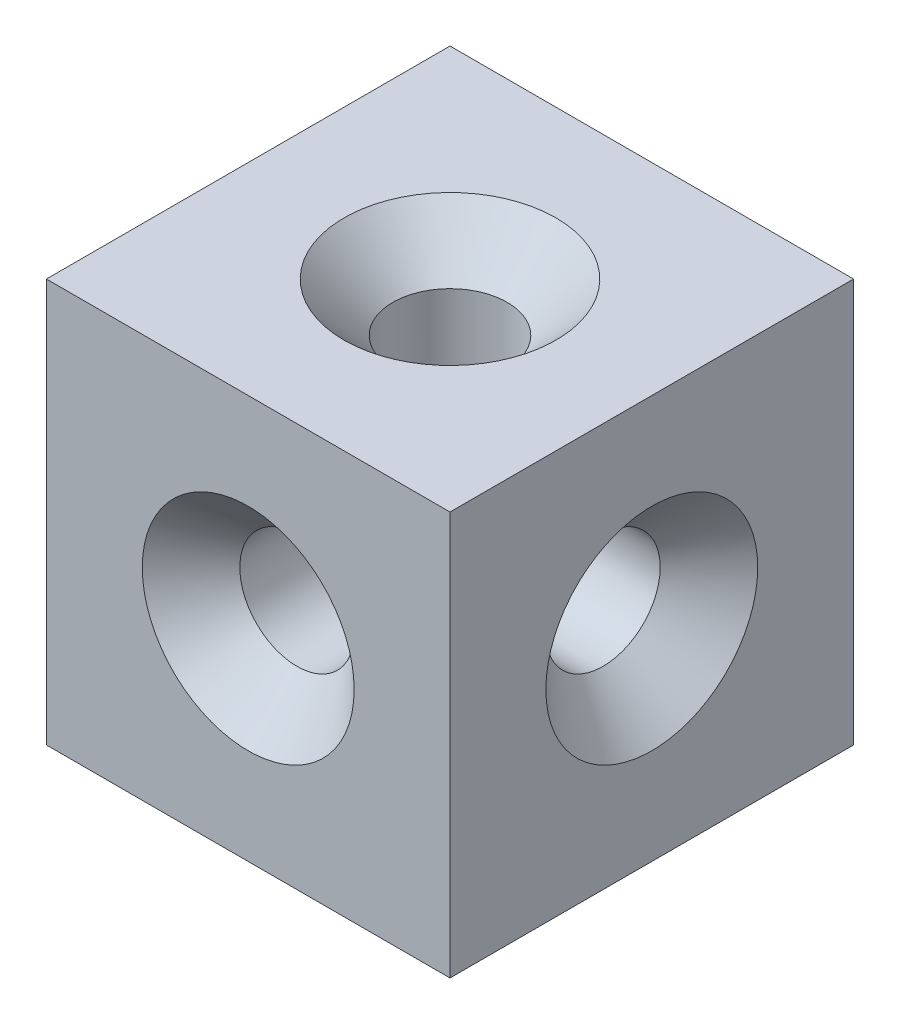
SolidWorks part; units mm, degrees
ref_plane "Front Plane" through (0, 0, 0) normal (0, 0, 1) x (1, 0, 0)
ref_plane "Top Plane" through (0, 0, 0) normal (0, 1, 0) x (1, 0, 0)
ref_plane "Right Plane" through (0, 0, 0) normal (1, 0, 0) x (0, 0, -1)
sketch "Sketch1" plane through (0, 0, 0) normal (0, 0, 1) x (1, 0, 0)
  line L1 (6, -6) -> (-6, -6)
  line L2 (6, -6) -> (6, 6)
  line L3 (6, 6) -> (-6, 6)
  line L4 (-6, -6) -> (-6, 6)
  line L5 (6, -6) -> (-6, 6) construction
  line L6 (6, 6) -> (-6, -6) construction
  point P0 (0, 0)
  dimension "D1" = 12
  dimension "D2" = 12
extrude "Boss-Extrude1" add sketch "Sketch1" along normal mid plane 12
hole_wizard "CSK for M3 Flat Head Machine Screw1" positions "Sketch3" profile "Sketch2" countersink size "M3" standard "ANSI Metric"
sketch "Sketch3" plane through (0, 0, 6) normal (0, 0, 1) x (1, 0, 0)
  point P0 (0, 0)
sketch "Sketch2" plane through (0, 0, 6) normal (1, 0, 0) x (0, -1, 0)
  line L0 (0, 0) -> (0, 7.0215)
  line L1 (0, 7.0215) -> (1.7, 6)
  line L2 (1.7, 6) -> (1.7, 1.45)
  line L3 (1.7, 1.45) -> (3.15, 0)
  line L5 (3.15, 0) -> (0, 0)
  line L6 (-1.7, 1.45) -> (-3.15, 0) construction
  line L10 (0, 7.0215) -> (-1.7, 6) construction
  line L11 (0, -6.35) -> (0, 107.95) construction
  dimension "Hole Dia." = 3.4
  dimension "Hole Depth" = 6
  dimension "Near C'Sink Dia." = 6.3
  dimension "Near C'Sink Angle" = 90
  dimension "Drill Angle" = 118
hole_wizard "CSK for M3 Flat Head Machine Screw2" positions "Sketch6" profile "Sketch7" countersink size "M3" standard "ANSI Metric"
sketch "Sketch6" plane through (6, 0, 0) normal (1, 0, 0) x (0, 0, -1)
  point P0 (0, 0)
sketch "Sketch7" plane through (6, 0, 0) normal (0, 1, 0) x (0, 0, -1)
  line L0 (0, 0) -> (0, 7.0215)
  line L1 (0, 7.0215) -> (1.7, 6)
  line L2 (1.7, 6) -> (1.7, 1.45)
  line L3 (1.7, 1.45) -> (3.15, 0)
  line L5 (3.15, 0) -> (0, 0)
  line L6 (-1.7, 1.45) -> (-3.15, 0) construction
  line L10 (0, 7.0215) -> (-1.7, 6) construction
  line L11 (0, -6.35) -> (0, 107.95) construction
  dimension "Hole Dia." = 3.4
  dimension "Hole Depth" = 6
  dimension "Near C'Sink Dia." = 6.3
  dimension "Near C'Sink Angle" = 90
  dimension "Drill Angle" = 118
hole_wizard "CSK for M3 Flat Head Machine Screw3" positions "Sketch8" profile "Sketch9" countersink size "M3" standard "ANSI Metric"
sketch "Sketch8" plane through (0, 0, -6) normal (0, 0, -1) x (-1, 0, 0)
  point P0 (0, 0)
sketch "Sketch9" plane through (0, 0, -6) normal (1, 0, 0) x (0, 1, 0)
  line L0 (0, 0) -> (0, 7.0215)
  line L1 (0, 7.0215) -> (1.7, 6)
  line L2 (1.7, 6) -> (1.7, 1.45)
  line L3 (1.7, 1.45) -> (3.15, 0)
  line L5 (3.15, 0) -> (0, 0)
  line L6 (-1.7, 1.45) -> (-3.15, 0) construction
  line L10 (0, 7.0215) -> (-1.7, 6) construction
  line L11 (0, -6.35) -> (0, 107.95) construction
  dimension "Hole Dia." = 3.4
  dimension "Hole Depth" = 6
  dimension "Near C'Sink Dia." = 6.3
  dimension "Near C'Sink Angle" = 90
  dimension "Drill Angle" = 118
hole_wizard "CSK for M3 Flat Head Machine Screw7" positions "Sketch10" profile "Sketch11" countersink size "M3" standard "ANSI Metric"
sketch "Sketch10" plane through (-6, 0, 0) normal (-1, 0, 0) x (0, 0, 1)
  point P0 (0, 0)
  point P4 (0, 0)
sketch "Sketch11" plane through (-6, 0, 0) normal (0, 1, 0) x (0, 0, 1)
  line L0 (0, 0) -> (0, 7.0215)
  line L1 (0, 7.0215) -> (1.7, 6)
  line L2 (1.7, 6) -> (1.7, 1.45)
  line L3 (1.7, 1.45) -> (3.15, 0)
  line L5 (3.15, 0) -> (0, 0)
  line L6 (-1.7, 1.45) -> (-3.15, 0) construction
  line L10 (0, 7.0215) -> (-1.7, 6) construction
  line L11 (0, -6.35) -> (0, 107.95) construction
  dimension "Hole Dia." = 3.4
  dimension "Hole Depth" = 6
  dimension "Near C'Sink Dia." = 6.3
  dimension "Near C'Sink Angle" = 90
  dimension "Drill Angle" = 118
hole_wizard "CSK for M3 Flat Head Machine Screw8" positions "Sketch12" profile "Sketch13" countersink size "M3" standard "ANSI Metric"
sketch "Sketch12" plane through (0, 6, 0) normal (0, 1, 0) x (1, 0, 0)
  point P0 (0, 0)
sketch "Sketch13" plane through (0, 6, 0) normal (1, 0, 0) x (0, 0, 1)
  line L0 (0, 0) -> (0, 7.0215)
  line L1 (0, 7.0215) -> (1.7, 6)
  line L2 (1.7, 6) -> (1.7, 1.45)
  line L3 (1.7, 1.45) -> (3.15, 0)
  line L5 (3.15, 0) -> (0, 0)
  line L6 (-1.7, 1.45) -> (-3.15, 0) construction
  line L10 (0, 7.0215) -> (-1.7, 6) construction
  line L11 (0, -6.35) -> (0, 107.95) construction
  dimension "Hole Dia." = 3.4
  dimension "Hole Depth" = 6
  dimension "Near C'Sink Dia." = 6.3
  dimension "Near C'Sink Angle" = 90
  dimension "Drill Angle" = 118
hole_wizard "CSK for M3 Flat Head Machine Screw9" positions "Sketch14" profile "Sketch15" countersink size "M3" standard "ANSI Metric"
sketch "Sketch14" plane through (0, -6, 0) normal (0, -1, 0) x (-1, 0, 0)
  point P0 (0, 0)
sketch "Sketch15" plane through (0, -6, 0) normal (1, 0, 0) x (0, 0, -1)
  line L0 (0, 0) -> (0, 7.0215)
  line L1 (0, 7.0215) -> (1.7, 6)
  line L2 (1.7, 6) -> (1.7, 1.45)
  line L3 (1.7, 1.45) -> (3.15, 0)
  line L5 (3.15, 0) -> (0, 0)
  line L6 (-1.7, 1.45) -> (-3.15, 0) construction
  line L10 (0, 7.0215) -> (-1.7, 6) construction
  line L11 (0, -6.35) -> (0, 107.95) construction
  dimension "Hole Dia." = 3.4
  dimension "Hole Depth" = 6
  dimension "Near C'Sink Dia." = 6.3
  dimension "Near C'Sink Angle" = 90
  dimension "Drill Angle" = 118
equation "\"Length\"= 283mm"
equation "\"Width\"= 225mm"
equation "\"WallThickness\"= 12.5mm"
equation "\"UpperWaterJacketThickness\"= 28mm"
equation "\"SpacerHeight\"= 80.2mm"
equation "\"SpacerCornerWidth\"= 10mm"
equation "\"SpacerCornerHeight\"= 60.16mm"
equation "\"SpacerPegDiameter\"= 10mm"
equation "\"SpacerPegHeight\"= 10mm"
equation "\"TubingShort\"= 110mm"
equation "\"TubingLong\"= 175mm"
equation "\"PlateLength\"= 252mm"
equation "\"PlateWidth\"= 190mm"
equation "\"PlateHoleDiameter\"= 5.9mm"
equation "\"PlateHoleBottom\"= 2mm"
equation "\"PlateHoleSide\"= 1.55mm"
equation "\"PlateHoleSpacing\"= 3.1mm"
equation "\"PlateThickness\"= 1.55mm"
equation "\"ReservoirBottom\"= 12.5mm"
equation "\"ReservoirSupportWidth\"= 12mm"
equation "\"ReservoirSupportHeight\"= 15.1mm"
equation "\"ReservoirSupportPlacementHeight\"= 50mm"
equation "\"ReservoirHoleDiameter\"= 12.7mm"
equation "\"ReservoirHoleRight\"= 25mm"
equation "\"ReservoirHoleTop\"= \"ReservoirSupportPlacementHeight\""
equation "\"ReservoirHeight\"= 90mm"
equation "\"ReservoirPortBottom\"= 4mm"
equation "\"ReservoirPortTop\"= 10mm"
equation "\"ReservoirPortWidth\"= 101mm"
equation "\"CustomSpacerWallThickness\"= 0.375in"
equation "\"CustomSpacerHeight\"= 5in"
equation "\"CustomSpacerRodHoleHeight\"= .75in"
equation "\"CustomSpacerRodHoleDiameter\"= .3125in"
equation "\"ScrewBlockSide\"= 12mm"
equation "\"ScrewBlockUpperHeight\"= 16mm"
equation "\"ScrewBlockLowerHeight\"= 16mm"
equation "\"InternalLength\"= \"Length\" - ( 2 * \"WallThickness\" )"
equation "\"InternalWidth\"= \"Width\" - ( 2 * \"WallThickness\" )"
equation "\"CustomSpacerPegHeight\"= 1in"
equation "\"CustomSpacerScrewBore\"=3.2mm"
equation "\"CustomSpacerScrewDepth\"=10mm"
equation "\"D1@Sketch1\"=\"ScrewBlockSide\""
equation "\"D2@Sketch1\"=\"ScrewBlockSide\""
equation "\"D1@Boss-Extrude1\"=\"ScrewBlockSide\""
